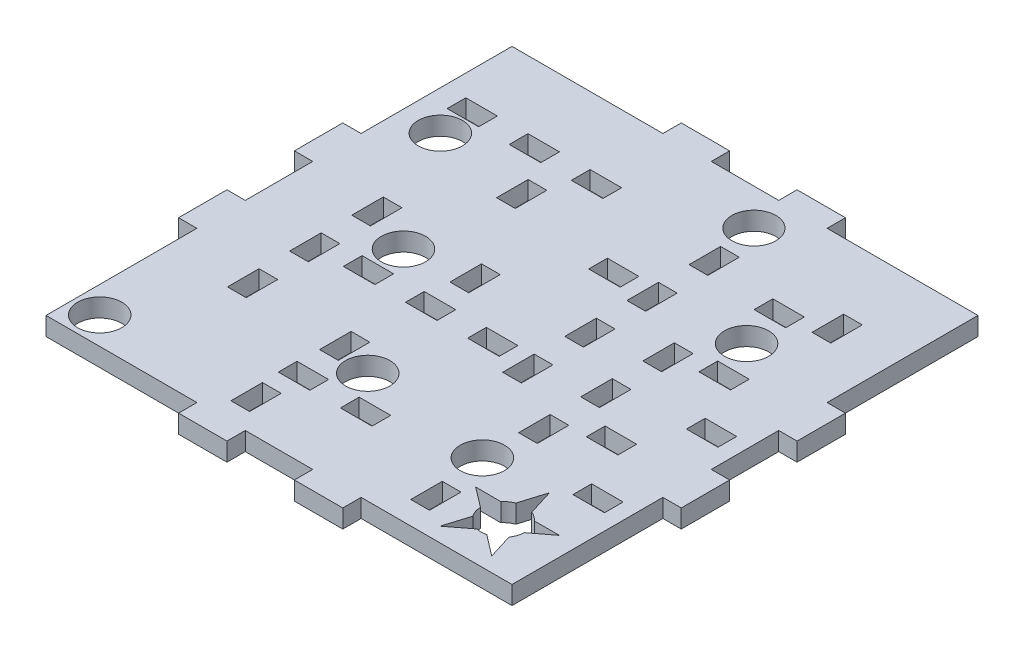
SolidWorks part; units mm, degrees
ref_plane "Front" through (0, 0, 0) normal (0, 0, 1) x (1, 0, 0)
ref_plane "Top" through (0, 0, 0) normal (0, 1, 0) x (1, 0, 0)
ref_plane "Right" through (0, 0, 0) normal (1, 0, 0) x (0, 0, -1)
sketch "Sketch1" plane through (0, 0, 0) normal (0, 1, 0) x (1, 0, 0)
  line L0 (-91.4768, 14.5899) -> (-91.4768, 55.7534)
  line L1 (-218.6038, 141.7169) -> (-177.4403, 141.7169)
  line L2 (-91.4768, 87.3534) -> (-91.4768, 68.9534)
  line L3 (-218.6038, 14.5899) -> (-177.4403, 14.5899)
  line L4 (-86.4768, 87.3534) -> (-86.4768, 100.5534)
  line L5 (-91.4768, 87.3534) -> (-86.4768, 87.3534)
  line L6 (-91.4768, 100.5534) -> (-86.4768, 100.5534)
  line L7 (-91.4768, 68.9534) -> (-86.4768, 68.9534)
  line L8 (-164.2403, 141.7169) -> (-145.8403, 141.7169)
  line L9 (-86.4768, 55.7534) -> (-86.4768, 68.9534)
  line L10 (-91.4768, 55.7534) -> (-86.4768, 55.7534)
  line L11 (-132.6403, 14.5899) -> (-132.6403, 9.5899)
  line L12 (-132.6403, 9.5899) -> (-145.8403, 9.5899)
  line L13 (-145.8403, 14.5899) -> (-145.8403, 9.5899)
  line L14 (-218.6038, 141.7169) -> (-218.6038, 100.5534)
  line L15 (-218.6038, 55.7534) -> (-218.6038, 14.5899)
  line L16 (-177.4403, 14.5899) -> (-177.4403, 9.5899)
  line L17 (-164.2403, 14.5899) -> (-164.2403, 9.5899)
  line L18 (-132.6403, 14.5899) -> (-91.4768, 14.5899)
  line L19 (-91.4768, 100.5534) -> (-91.4768, 141.7169)
  line L20 (-164.2403, 9.5899) -> (-177.4403, 9.5899)
  line L21 (-103.4537, 32.6445) -> (-96.5905, 32.6584)
  line L22 (-164.2403, 14.5899) -> (-145.8403, 14.5899)
  line L23 (-132.6403, 141.7169) -> (-91.4768, 141.7169)
  line L24 (-96.5905, 32.6584) -> (-102.0315, 28.5187)
  line L25 (-103.0822, 25.3647) -> (-100.9563, 18.5301)
  line L26 (-100.9563, 18.5301) -> (-106.6783, 22.9191)
  line L27 (-109.3628, 22.919) -> (-115.0847, 18.5301)
  line L28 (-115.0847, 18.5301) -> (-112.9588, 25.3647)
  line L29 (-114.0095, 28.5187) -> (-119.4505, 32.6584)
  line L30 (-119.4505, 32.6584) -> (-112.5873, 32.6445)
  line L31 (-110.1801, 34.3554) -> (-108.0205, 41.3901)
  line L32 (-108.0205, 41.3901) -> (-105.8609, 34.3554)
  line L33 (-173.5266, 37.9948) -> (-173.5266, 32.8948)
  line L34 (-173.5266, 37.9948) -> (-164.9259, 37.9948)
  line L35 (-173.5266, 32.8948) -> (-164.9259, 32.8948)
  line L36 (-164.9259, 32.8948) -> (-164.9259, 37.9948)
  line L37 (-156.5791, 32.8948) -> (-156.5791, 37.9948)
  line L38 (-156.5791, 37.9948) -> (-147.9749, 37.9948)
  line L39 (-156.5791, 32.8948) -> (-147.9749, 32.8948)
  line L40 (-147.9749, 37.9948) -> (-147.9749, 32.8948)
  line L41 (-121.3307, 51.3439) -> (-126.4307, 51.3439)
  line L43 (-126.4307, 51.3439) -> (-126.4307, 59.9446)
  line L44 (-121.3307, 51.3439) -> (-121.3307, 59.9446)
  line L45 (-121.3307, 59.9446) -> (-126.4307, 59.9446)
  line L46 (-121.3307, 68.2914) -> (-126.4307, 68.2914)
  line L47 (-126.4307, 68.2914) -> (-126.4307, 76.8956)
  line L48 (-121.3307, 68.2914) -> (-121.3307, 76.8956)
  line L49 (-121.3307, 76.8956) -> (-126.4307, 76.8956)
  line L50 (-121.3307, 85.2423) -> (-126.4307, 85.2423)
  line L51 (-126.4307, 85.2423) -> (-126.4307, 93.8466)
  line L52 (-121.3307, 85.2423) -> (-121.3307, 93.8466)
  line L55 (-121.3307, 93.8466) -> (-126.4307, 93.8466)
  line L56 (-116.217, 90.3341) -> (-116.217, 95.4341)
  line L58 (-116.217, 95.4341) -> (-107.6163, 95.4341)
  line L61 (-164.2403, 146.7169) -> (-177.4403, 146.7169)
  line L62 (-116.217, 90.3341) -> (-107.6163, 90.3341)
  line L63 (-107.6163, 90.3341) -> (-107.6163, 95.4341)
  line L64 (-116.217, 64.7257) -> (-116.217, 59.6257)
  line L65 (-116.217, 59.6257) -> (-107.6163, 59.6257)
  line L66 (-116.217, 64.7257) -> (-107.6163, 64.7257)
  line L67 (-107.6163, 64.7257) -> (-107.6163, 59.6257)
  line L68 (-104.4039, 75.1053) -> (-104.4039, 80.2053)
  line L69 (-104.4039, 80.2053) -> (-95.8032, 80.2053)
  line L70 (-104.4039, 75.1053) -> (-95.8032, 75.1053)
  line L71 (-95.8032, 75.1053) -> (-95.8032, 80.2053)
  line L72 (-164.2403, 141.7169) -> (-164.2403, 146.7169)
  line L73 (-177.4403, 141.7169) -> (-177.4403, 146.7169)
  line L74 (-104.4039, 49.2315) -> (-104.4039, 44.1315)
  line L75 (-104.4039, 44.1315) -> (-95.8032, 44.1315)
  line L76 (-145.8403, 141.7169) -> (-145.8403, 146.7169)
  line L77 (-104.4039, 49.2315) -> (-95.8032, 49.2315)
  line L78 (-132.6403, 146.7169) -> (-145.8403, 146.7169)
  line L79 (-132.6403, 141.7169) -> (-132.6403, 146.7169)
  line L82 (-95.8032, 49.2315) -> (-95.8032, 44.1315)
  line L84 (-125.3604, 20.8539) -> (-120.2604, 20.8539)
  line L85 (-120.2604, 20.8539) -> (-120.2604, 29.4546)
  line L88 (-125.3604, 20.8539) -> (-125.3604, 29.4546)
  line L89 (-125.3604, 29.4546) -> (-120.2604, 29.4546)
  line L90 (-123.3893, 112.5551) -> (-123.3893, 117.6551)
  line L91 (-123.3893, 117.6551) -> (-114.7886, 117.6551)
  line L92 (-123.3893, 112.5551) -> (-114.7886, 112.5551)
  line L93 (-114.7886, 112.5551) -> (-114.7886, 117.6551)
  line L94 (-105.0183, 115.096) -> (-110.1183, 115.096)
  line L95 (-110.1183, 115.096) -> (-110.1183, 123.6967)
  line L96 (-105.0183, 115.096) -> (-105.0183, 123.6967)
  line L97 (-105.0183, 123.6967) -> (-110.1183, 123.6967)
  line L98 (-168.1184, 19.6544) -> (-173.2184, 19.6544)
  line L99 (-173.2184, 19.6544) -> (-173.2184, 28.2551)
  line L100 (-168.1184, 19.6544) -> (-168.1184, 28.2551)
  line L101 (-168.1184, 28.2551) -> (-173.2184, 28.2551)
  line L102 (-168.1172, 43.836) -> (-173.2172, 43.836)
  line L103 (-173.2172, 43.836) -> (-173.2172, 52.4367)
  line L104 (-168.1172, 43.836) -> (-168.1172, 52.4367)
  line L105 (-168.1172, 52.4367) -> (-173.2172, 52.4367)
  line L106 (-137.7867, 63.4542) -> (-142.8867, 63.4542)
  line L107 (-142.8867, 63.4542) -> (-142.8867, 72.0549)
  line L108 (-137.7867, 63.4542) -> (-137.7867, 72.0549)
  line L109 (-137.7867, 72.0549) -> (-142.8867, 72.0549)
  line L110 (-137.7867, 80.4017) -> (-142.8867, 80.4017)
  line L111 (-142.8867, 80.4017) -> (-142.8867, 89.0059)
  line L112 (-137.7867, 80.4017) -> (-137.7867, 89.0059)
  line L113 (-137.7867, 89.0059) -> (-142.8867, 89.0059)
  line L114 (-137.7867, 97.3526) -> (-142.8867, 97.3526)
  line L115 (-142.8867, 97.3526) -> (-142.8867, 105.9569)
  line L116 (-137.7867, 97.3526) -> (-137.7867, 105.9569)
  line L117 (-137.7867, 105.9569) -> (-142.8867, 105.9569)
  line L118 (-137.7867, 114.3036) -> (-142.8867, 114.3036)
  line L119 (-142.8867, 114.3036) -> (-142.8867, 122.9043)
  line L120 (-137.7867, 114.3036) -> (-137.7867, 122.9043)
  line L121 (-137.7867, 122.9043) -> (-142.8867, 122.9043)
  line L122 (-166.2924, 77.5862) -> (-171.3924, 77.5862)
  line L123 (-171.3924, 77.5862) -> (-171.3924, 86.1869)
  line L124 (-166.2924, 77.5862) -> (-166.2924, 86.1869)
  line L125 (-166.2924, 86.1869) -> (-171.3924, 86.1869)
  line L126 (-179.8524, 103.859) -> (-184.9524, 103.859)
  line L127 (-184.9524, 103.859) -> (-184.9524, 112.4597)
  line L128 (-179.8524, 103.859) -> (-179.8524, 112.4597)
  line L129 (-179.8524, 112.4597) -> (-184.9524, 112.4597)
  line L130 (-146.9584, 104.689) -> (-146.9584, 99.589)
  line L131 (-146.9584, 99.589) -> (-155.5591, 99.589)
  line L132 (-146.9584, 104.689) -> (-155.5591, 104.689)
  line L133 (-155.5591, 104.689) -> (-155.5591, 99.589)
  line L134 (-189.6236, 66.7312) -> (-189.6236, 71.8312)
  line L135 (-189.6236, 71.8312) -> (-181.0229, 71.8312)
  line L136 (-189.6236, 66.7312) -> (-181.0229, 66.7312)
  line L137 (-181.0229, 66.7312) -> (-181.0229, 71.8312)
  line L138 (-172.6761, 66.7312) -> (-172.6761, 71.8312)
  line L139 (-172.6761, 71.8312) -> (-164.0719, 71.8312)
  line L140 (-172.6761, 66.7312) -> (-164.0719, 66.7312)
  line L141 (-164.0719, 66.7312) -> (-164.0719, 71.8312)
  line L142 (-155.7252, 66.7312) -> (-155.7252, 71.8312)
  line L143 (-155.7252, 71.8312) -> (-147.1209, 71.8312)
  line L144 (-155.7252, 66.7312) -> (-147.1209, 66.7312)
  line L145 (-147.1209, 66.7312) -> (-147.1209, 71.8312)
  line L146 (-195.4854, 46.0847) -> (-200.5854, 46.0847)
  line L147 (-200.5854, 46.0847) -> (-200.5854, 54.6854)
  line L148 (-195.4854, 46.0847) -> (-195.4854, 54.6854)
  line L149 (-195.4854, 54.6854) -> (-200.5854, 54.6854)
  line L150 (-195.4854, 63.0322) -> (-200.5854, 63.0322)
  line L151 (-200.5854, 63.0322) -> (-200.5854, 71.6364)
  line L152 (-195.4854, 63.0322) -> (-195.4854, 71.6364)
  line L153 (-195.4854, 71.6364) -> (-200.5854, 71.6364)
  line L154 (-195.4854, 79.9831) -> (-200.5854, 79.9831)
  line L155 (-200.5854, 79.9831) -> (-200.5854, 88.5874)
  line L156 (-195.4854, 79.9831) -> (-195.4854, 88.5874)
  line L157 (-195.4854, 88.5874) -> (-200.5854, 88.5874)
  line L158 (-170.2578, 123.2723) -> (-170.2578, 118.1723)
  line L159 (-170.2578, 118.1723) -> (-178.8585, 118.1723)
  line L160 (-170.2578, 123.2723) -> (-178.8585, 123.2723)
  line L161 (-178.8585, 123.2723) -> (-178.8585, 118.1723)
  line L162 (-187.2053, 123.2723) -> (-187.2053, 118.1723)
  line L163 (-187.2053, 118.1723) -> (-195.8095, 118.1723)
  line L164 (-187.2053, 123.2723) -> (-195.8095, 123.2723)
  line L165 (-195.8095, 123.2723) -> (-195.8095, 118.1723)
  line L166 (-204.1562, 123.2723) -> (-204.1562, 118.1723)
  line L167 (-204.1562, 118.1723) -> (-212.7605, 118.1723)
  line L168 (-204.1562, 123.2723) -> (-212.7605, 123.2723)
  line L169 (-212.7605, 123.2723) -> (-212.7605, 118.1723)
  line L177 (-218.6038, 68.9534) -> (-218.6038, 87.3534)
  line L178 (-223.6038, 68.9534) -> (-223.6038, 55.7534)
  line L179 (-218.6038, 68.9534) -> (-223.6038, 68.9534)
  line L180 (-218.6038, 55.7534) -> (-223.6038, 55.7534)
  line L181 (-218.6038, 87.3534) -> (-223.6038, 87.3534)
  line L182 (-223.6038, 100.5534) -> (-223.6038, 87.3534)
  line L183 (-218.6038, 100.5534) -> (-223.6038, 100.5534)
  circle A0 centre (-142.6785, 131.7801) radius 6
  circle A1 centre (-207.8781, 111.4392) radius 6.0325
  circle A2 centre (-116.3981, 103.5045) radius 6.0325
  circle A3 centre (-125.4239, 40.4535) radius 6.0325
  circle A4 centre (-161.0523, 44.8095) radius 6.0325
  circle A5 centre (-185.5281, 79.0317) radius 6.0325
  circle A6 centre (-211.3947, 22.0311) radius 6.0325
  spline S0 degree 3 poles (-105.8609, 34.3554) (-104.921, 33.9921) (-104.0956, 33.3988) (-103.4537, 32.6445) knots 0 0 0 0 0.058824 0.058824 0.058824 0.058824
  spline S1 degree 3 poles (-102.0315, 28.5187) (-102.0782, 27.3503) (-102.4595, 26.268) (-103.0822, 25.3647) knots 0.176471 0.176471 0.176471 0.176471 0.235294 0.235294 0.235294 0.235294
  spline S2 degree 3 poles (-106.6783, 22.9191) (-107.1099, 22.8203) (-107.5591, 22.768) (-108.0206, 22.768) knots 0.352941 0.352941 0.352941 0.352941 0.411765 0.411765 0.411765 0.411765
  spline S3 degree 3 poles (-108.0206, 22.768) (-108.482, 22.768) (-108.9313, 22.8203) (-109.3628, 22.919) knots 0.411765 0.411765 0.411765 0.411765 0.470588 0.470588 0.470588 0.470588
  spline S4 degree 3 poles (-112.9588, 25.3647) (-113.5815, 26.2679) (-113.9627, 27.3503) (-114.0095, 28.5187) knots 0.588235 0.588235 0.588235 0.588235 0.647059 0.647059 0.647059 0.647059
  spline S5 degree 3 poles (-112.5873, 32.6445) (-111.9454, 33.3989) (-111.1199, 33.9921) (-110.1801, 34.3554) knots 0.764706 0.764706 0.764706 0.764706 0.823529 0.823529 0.823529 0.823529
extrude "Boss-Extrude1" add sketch "Sketch1" along normal blind 5
